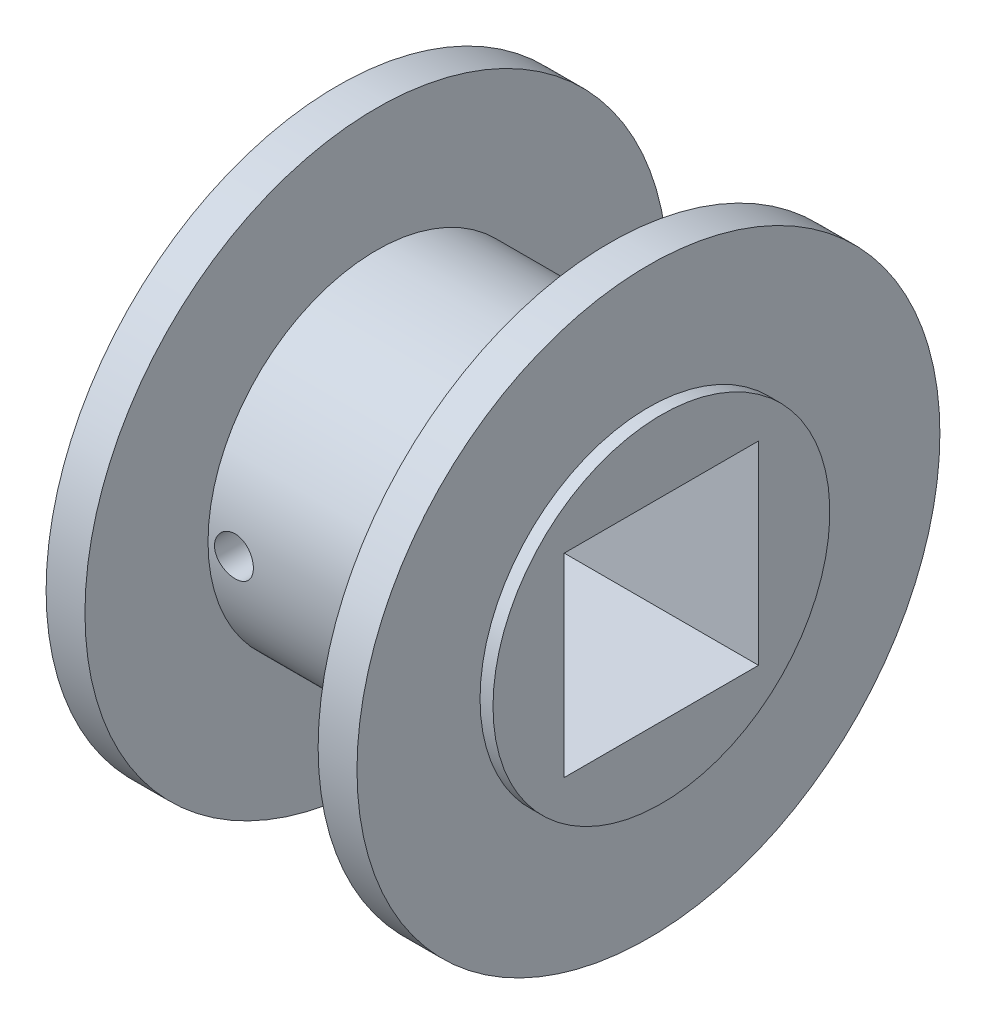
SolidWorks part; units mm, degrees
ref_plane "Front Plane" through (0, 0, 0) normal (0, 0, 1) x (1, 0, 0)
ref_plane "Top Plane" through (0, 0, 0) normal (0, 1, 0) x (1, 0, 0)
ref_plane "Right Plane" through (0, 0, 0) normal (1, 0, 0) x (0, 0, -1)
sketch "Sketch1" plane through (0, 0, 0) normal (0, 0, 1) x (1, 0, 0)
  line L0 (0, 0) -> (28.5911, 0) construction
  line L1 (0, 7.5) -> (26, 7.5)
  line L2 (4, 13) -> (22, 13)
  line L3 (1, 22.5) -> (4, 22.5)
  line L4 (25, 22.5) -> (22, 22.5)
  line L5 (4, 22.5) -> (4, 13)
  line L6 (1, 22.5) -> (1, 13)
  line L7 (1, 13) -> (0, 13)
  line L8 (0, 13) -> (0, 7.5)
  line L9 (22, 22.5) -> (22, 13)
  line L10 (25, 22.5) -> (25, 13)
  line L11 (25, 13) -> (26, 13)
  line L12 (26, 13) -> (26, 7.5)
  point P19 (13, 13)
  point P20 (13, 7.5)
  dimension "D1" = 15
  dimension "D2" = 26
  dimension "D3" = 45
  dimension "D5" = 18
  dimension "D6" = 3
  dimension "D7" = 3
  dimension "D8" = 26
revolve "Revolve1" add sketch "Sketch1" angle 360 about L0
sketch "Sketch2" plane through (26, 0, 0) normal (1, 0, 0) x (0, 0, -1)
  line L0 (-7.5, 7.5) -> (7.5, -7.5)
  line L1 (-7.5, 7.5) -> (7.5, 7.5)
  line L2 (-7.5, 7.5) -> (-7.5, -7.5)
  line L3 (-7.5, -7.5) -> (7.5, -7.5)
  line L4 (7.5, 7.5) -> (7.5, -7.5)
  circle A0 centre (0, 0) radius 7.5 construction
  point P7 (0, 0)
  circle M7 centre (0, 0) radius 7.5
  dimension "D1" = 15
extrude "Cut-Extrude1" cut sketch "Sketch2" against normal through all contours L0 M7 | L1 L0 M7 | L4 L1 M7 | L4 L0 M7 | L3 L0 M7 | L2 L3 M7 | L0 M7 | L0 L2 M7
sketch "Sketch3" plane through (0, 0, 7.5) normal (0, 0, -1) x (-1, 0, 0)
  line L0 (0, 7.5) -> (0, -7.5) construction
  line L1 (0, 7.5) -> (0, -7.5)
  line L2 (0, 0) -> (-6, 0)
  circle A0 centre (-6, 0) radius 1.5
  dimension "D2" = 3
  dimension "D1" = 6
extrude "Cut-Extrude2" cut sketch "Sketch3" against normal through all
